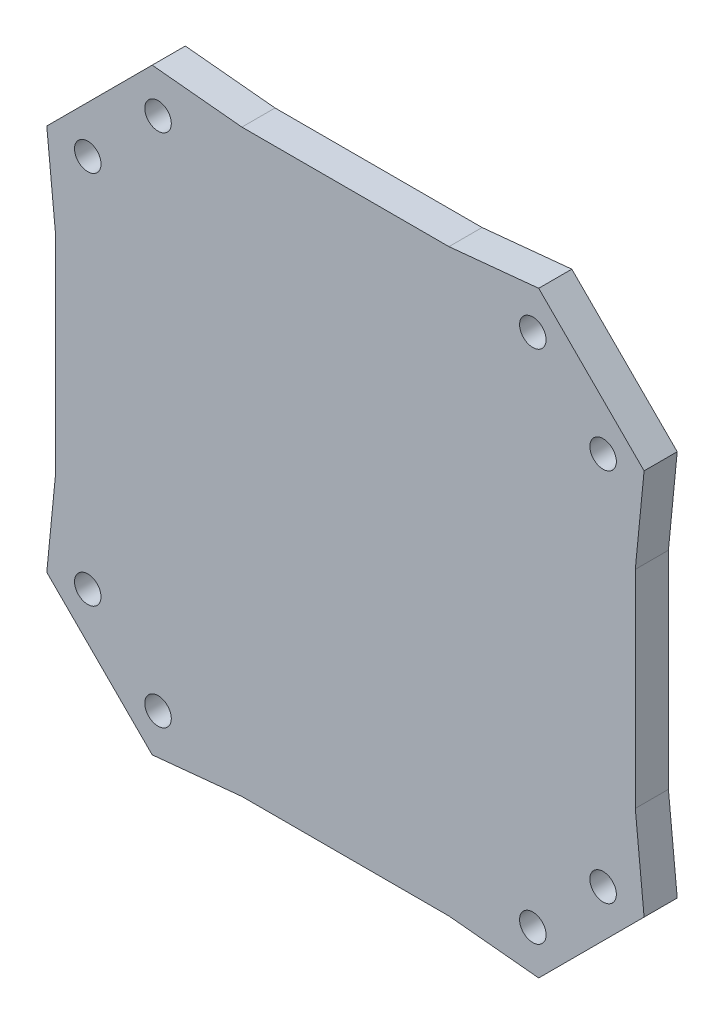
SolidWorks part; units mm, degrees
ref_plane "Front Plane" through (0, 0, 0) normal (0, 0, 1) x (1, 0, 0)
ref_plane "Top Plane" through (0, 0, 0) normal (0, 1, 0) x (1, 0, 0)
ref_plane "Right Plane" through (0, 0, 0) normal (1, 0, 0) x (0, 0, -1)
sketch "Sketch1" plane through (0, 0, 0) normal (0, 0, 1) x (1, 0, 0)
  line L0 (-35, 35) -> (-35, -35) construction
  line L1 (-35, -35) -> (35, -35) construction
  line L2 (35, -35) -> (35, 35) construction
  line L3 (-35, 35) -> (35, 35) construction
  line L4 (-35, 35) -> (35, -35) construction
  line L5 (35, 35) -> (-35, -35) construction
  line L6 (0, 0) -> (0, 35) construction
  line L7 (0, 0) -> (0, -35) construction
  line L8 (12.5, 35) -> (-12.5, 35)
  line L9 (0, 0) -> (84.8528, 84.8528) construction
  line L10 (23.3345, 36.0624) -> (36.0624, 23.3345)
  line L11 (20.5061, 33.234) -> (33.234, 20.5061) construction
  line L12 (12.5, 35) -> (23.3345, 36.0624)
  line L13 (35, -12.5) -> (36.0624, -23.3345)
  line L14 (35, -12.5) -> (35, 12.5)
  line L15 (-12.5, -35) -> (-23.3345, -36.0624)
  line L16 (-12.5, -35) -> (12.5, -35)
  line L17 (-35, 12.5) -> (-36.0624, 23.3345)
  line L18 (-35, 12.5) -> (-35, -12.5)
  line L19 (36.0624, 23.3345) -> (35, 12.5)
  line L21 (-23.3345, -36.0624) -> (-36.0624, -23.3345)
  line L22 (-36.0624, 23.3345) -> (-23.3345, 36.0624)
  line L23 (36.0624, -23.3345) -> (23.3345, -36.0624)
  line L24 (23.3345, -36.0624) -> (12.5, -35)
  line L26 (-36.0624, -23.3345) -> (-35, -12.5)
  line L28 (-23.3345, 36.0624) -> (-12.5, 35)
  line L29 (36.0624, -23.3345) -> (23.3345, -36.0624) [skipped]
  line L30 (-23.3345, -36.0624) -> (-36.0624, -23.3345) [skipped]
  line L31 (-36.0624, 23.3345) -> (-23.3345, 36.0624) [skipped]
  circle A0 centre (22.6274, 31.1127) radius 1.6
  circle A1 centre (31.1127, 22.6274) radius 1.6
  circle A8 centre (22.6274, -31.1127) radius 1.6
  circle A9 centre (31.1127, -22.6274) radius 1.6
  circle A10 centre (-31.1127, -22.6274) radius 1.6
  circle A11 centre (-22.6274, -31.1127) radius 1.6
  circle A12 centre (-22.6274, 31.1127) radius 1.6
  circle A13 centre (-31.1127, 22.6274) radius 1.6
  circle A14 centre (22.6274, -31.1127) radius 1.6 [skipped]
  circle A15 centre (31.1127, -22.6274) radius 1.6 [skipped]
  circle A16 centre (-31.1127, -22.6274) radius 1.6 [skipped]
  circle A17 centre (-22.6274, -31.1127) radius 1.6 [skipped]
  circle A18 centre (-22.6274, 31.1127) radius 1.6 [skipped]
  circle A19 centre (-31.1127, 22.6274) radius 1.6 [skipped]
  point P3 (0, 0)
  point P11 (0, 35)
  point P17 (29.6985, 29.6985)
  dimension "D15" = 3.2
  dimension "D16" = 3.2
  dimension "D1" = 70
  dimension "D2" = 70
  dimension "D3" = 25
  dimension "D4" = 120
  dimension "D5" = 78
  dimension "D6" = 18
  dimension "D7" = 9
  dimension "D8" = 4
  dimension "D9" = 82
  dimension "D10" = 18
  dimension "D11" = 9
  dimension "D13" = 6
  dimension "D14" = 6
  dimension "D12" = 4
  dimension "D17" = 4
  dimension "D18" = 4
extrude "Boss-Extrude1" add sketch "Sketch1" along normal blind 4
sketch "Sketch2" plane through (0, 0, 4) normal (0, 0, 1) x (1, 0, 0)
  line L0 (-29, 13.1477) -> (-29, -14.91)
  line L1 (-29, -14.91) -> (-17.0318, -26.8782)
  line L2 (-17.0318, -26.8782) -> (12.062, -26.8782)
  line L3 (12.062, -26.8782) -> (26.2153, -18.7314)
  line L4 (26.2153, -18.7314) -> (26.2153, 17.9173)
  line L5 (26.2153, 17.9173) -> (15.6661, 28.4665)
  line L6 (15.6661, 28.4665) -> (-18.5093, 28.4665)
  line L7 (-18.5093, 28.4665) -> (-29, 13.1477)
  line L8 (0, 0) -> (-70.6959, 0) construction
  line L9 (0, 0) -> (61.9212, 0) construction
  line L10 (-35, 12.5) -> (-35, -12.5) construction
  dimension "D1" = 6
